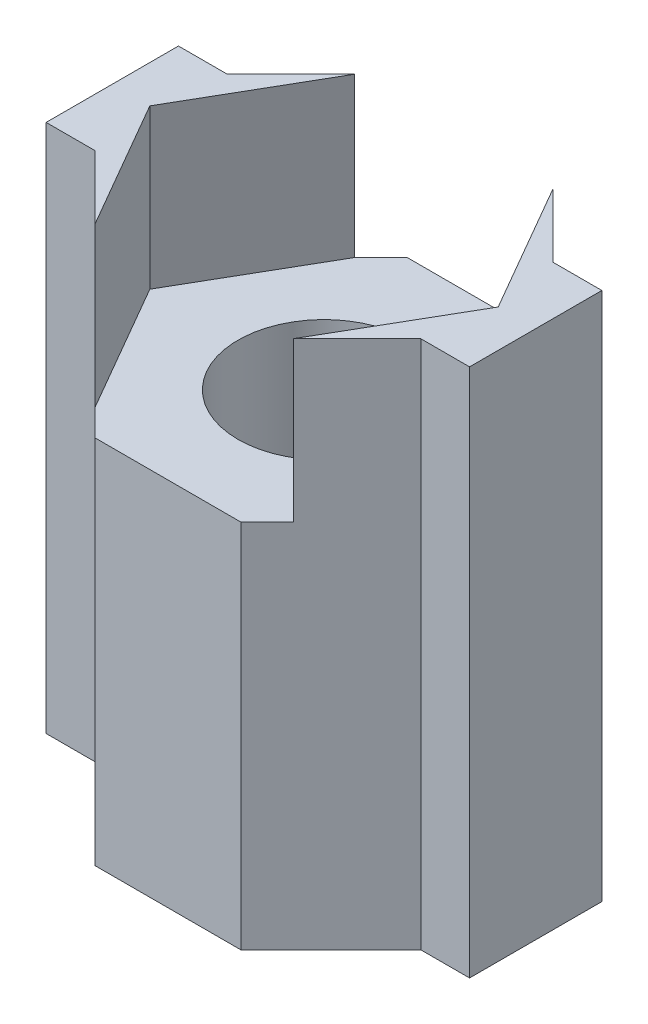
SolidWorks part; units mm, degrees
ref_plane "Plano frontal" through (0, 0, 0) normal (0, 0, 1) x (1, 0, 0)
ref_plane "Plano superior" through (0, 0, 0) normal (0, 1, 0) x (1, 0, 0)
ref_plane "Plano direito" through (0, 0, 0) normal (1, 0, 0) x (0, 0, -1)
sketch "Esboço1" plane through (0, 0, 0) normal (0, 1, 0) x (1, 0, 0)
  line L0 (-2.8393, 6.1) -> (2.8393, 6.1) construction
  line L1 (2.8393, 6.1) -> (6.2393, 2.7) construction
  line L2 (6.2393, 2.7) -> (8.2, 2.7) construction
  line L3 (8.2, 2.7) -> (8.2, -2.7) construction
  line L4 (8.2, -2.7) -> (6.2393, -2.7) construction
  line L5 (6.2393, -2.7) -> (2.8393, -6.1) construction
  line L6 (2.8393, -6.1) -> (-2.8393, -6.1) construction
  line L7 (-2.8393, -6.1) -> (-6.2393, -2.7) construction
  line L8 (-6.2393, -2.7) -> (-8.2, -2.7) construction
  line L9 (-8.2, -2.7) -> (-8.2, 2.7) construction
  line L10 (-8.2, 2.7) -> (-6.2393, 2.7) construction
  line L11 (-6.2393, 2.7) -> (-2.8393, 6.1) construction
  line L12 (-8, 2.5) -> (-6.1565, 2.5)
  line L13 (-6.1565, 2.5) -> (-2.7565, 5.9)
  line L14 (-2.7565, 5.9) -> (2.7565, 5.9)
  line L15 (2.7565, 5.9) -> (6.1565, 2.5)
  line L16 (6.1565, 2.5) -> (8, 2.5)
  line L17 (8, 2.5) -> (8, -2.5)
  line L18 (8, -2.5) -> (6.1565, -2.5)
  line L19 (6.1565, -2.5) -> (2.7565, -5.9)
  line L20 (2.7565, -5.9) -> (-2.7565, -5.9)
  line L21 (-2.7565, -5.9) -> (-6.1565, -2.5)
  line L22 (-6.1565, -2.5) -> (-8, -2.5)
  line L23 (-8, -2.5) -> (-8, 2.5)
  dimension "D1" = 0.2
extrude "Ressalto-extrusão1" add sketch "Esboço1" along normal blind 20
sketch "Esboço2" plane through (0, 20, 0) normal (0, 1, 0) x (1, 0, 0)
  line L0 (-3.2909, 5.7) -> (-3.2909, 6.5589)
  line L1 (3.2909, -5.7) -> (6.5818, 0)
  line L2 (6.5818, 0) -> (3.2909, 5.7)
  line L3 (3.2909, 5.7) -> (-3.2909, 5.7) construction
  line L4 (-3.2909, 5.7) -> (-6.5818, 0)
  line L5 (-6.5818, 0) -> (-3.2909, -5.7)
  line L6 (-3.2909, -5.7) -> (3.2909, -5.7) construction
  line L7 (-3.2909, 6.5589) -> (3.2909, 6.5589)
  line L8 (3.2909, 6.5589) -> (3.2909, 5.7)
  line L9 (-3.2909, -5.7) -> (-3.2909, -6.5589)
  line L10 (-3.2909, -6.5589) -> (3.2909, -6.5589)
  line L11 (3.2909, -6.5589) -> (3.2909, -5.7)
  circle A0 centre (0, 0) radius 5.7 construction
  dimension "D1" = 11.4
extrude "Corte-extrusão1" cut sketch "Esboço2" against normal blind 6
sketch "Esboço3" plane through (0, 14, 0) normal (0, 1, 0) x (1, 0, 0)
  circle A0 centre (0, 0) radius 3.25
  dimension "D1" = 6.5
extrude "Corte-extrusão2" cut sketch "Esboço3" against normal through all
